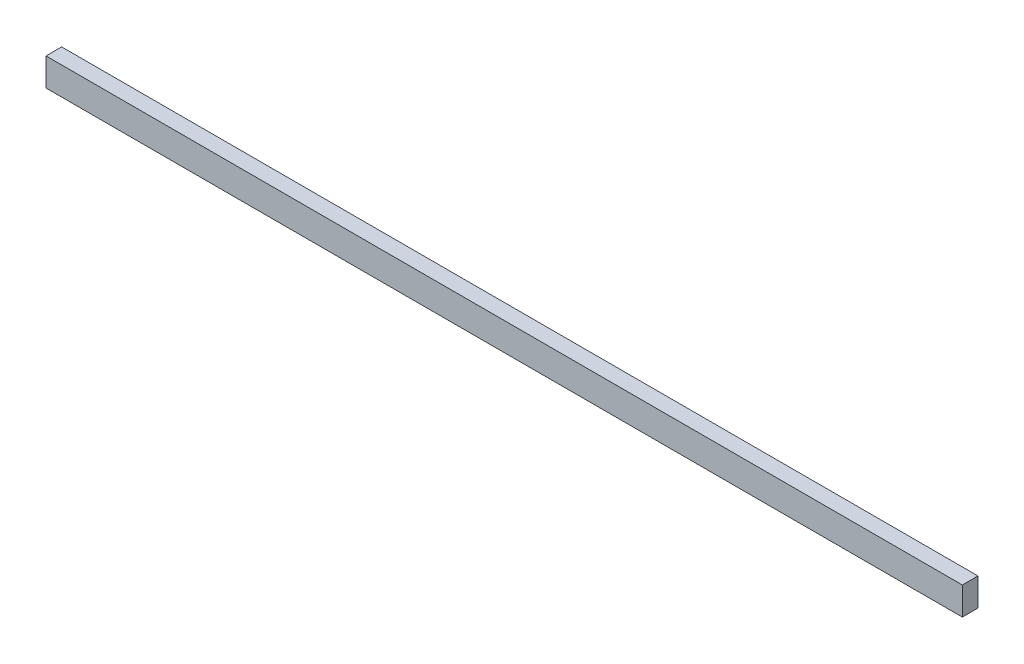
SolidWorks part; units mm, degrees
ref_plane "Front Plane" through (0, 0, 0) normal (0, 0, 1) x (1, 0, 0)
ref_plane "Top Plane" through (0, 0, 0) normal (0, 1, 0) x (1, 0, 0)
ref_plane "Right Plane" through (0, 0, 0) normal (1, 0, 0) x (0, 0, -1)
sketch "Sketch2" plane through (0, 0, 0) normal (1, 0, 0) x (0, 0, -1)
  line L1 (0, 0) -> (9, 0)
  line L2 (0, 0) -> (0, 16)
  line L3 (0, 16) -> (9, 16)
  line L4 (9, 0) -> (9, 16)
  dimension "D1" = 16
  dimension "D2" = 9
extrude "Boss-Extrude1" add sketch "Sketch2" along normal blind 527
ref_plane "Plane1" through (0, 8, 0) normal (0, 1, 0) x (1, 0, 0)
